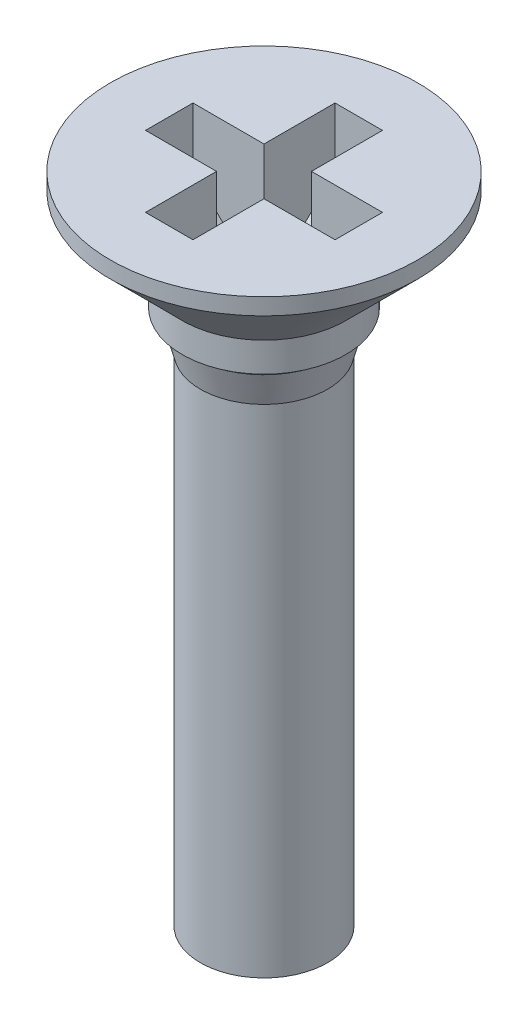
SolidWorks part; units mm, degrees
ref_plane "Vorderseite" through (0, 0, 0) normal (0, 0, 1) x (1, 0, 0)
ref_plane "Oben" through (0, 0, 0) normal (0, 1, 0) x (1, 0, 0)
ref_plane "Rechts" through (0, 0, 0) normal (1, 0, 0) x (0, 0, -1)
sketch "Skizze1" plane through (0, 0, 0) normal (0, 0, 1) x (1, 0, 0)
  line L0 (0, 0) -> (2.35, 0)
  line L1 (2.35, 0) -> (2.35, -0.254)
  line L2 (2.35, -0.254) -> (1.25, -1.354)
  line L3 (1.104, -1.804) -> (1.104, -1.9148)
  line L4 (1.104, -1.9148) -> (0.974, -2.4)
  line L5 (0.974, -2.4) -> (0.974, -10)
  line L6 (0.974, -10) -> (0, -10)
  line L7 (0, 0) -> (0, -10) construction
  line L8 (0, 0) -> (0, -10)
  line L10 (1.25, -1.354) -> (1.25, -1.804)
  line L12 (1.25, -1.804) -> (1.104, -1.804)
  point P3 (1.104, -1.5)
  dimension "D1" = 45
  dimension "D2" = 15
  dimension "K" = 1.5
  dimension "DA" = 4.7
  dimension "DK" = 1.948
  dimension "L" = 10
  dimension "DG" = 2.5
  dimension "A" = 0.9
  dimension "DF" = 2.208
  dimension "P" = 0.45
revolve "Basis-Rotation" add sketch "Skizze1" angle 360 about L7
sketch "Skizze2" plane through (0, 0, 0) normal (0, 0, 1) x (1, 0, 0)
  line L0 (0, -1.8) -> (0, 0) construction
  line L1 (0, 0) -> (0, -10) construction
  line L2 (-0.55, -1.8) -> (0.55, -1.8)
  line L3 (1.45, 0) -> (1.45, -0.9)
  line L4 (1.45, -0.9) -> (0.55, -1.8)
  line L5 (1.45, 0) -> (-1.45, 0)
  line L6 (-1.45, -0.9) -> (-0.55, -1.8)
  line L7 (-1.45, 0) -> (-1.45, -0.9)
  line L8 (0, -0.9) -> (1.45, -0.9) construction
  line L9 (2.35, 0) -> (-2.35, 0) construction
  line L11 (1.25, -1.354) -> (2.35, -0.254) construction
  point P11 (0, 0)
  dimension "M" = 2.9
  dimension "T" = 1.8
extrude "Kreuzschlitz1 H" cut sketch "Skizze2" against normal blind 0.363 and the other way blind 0.363
sketch "Skizze3" plane through (0, 0, 0) normal (1, 0, 0) x (0, 0, -1)
  line L0 (0, -1.8) -> (0, 0) construction
  line L2 (-0.55, -1.8) -> (0.55, -1.8)
  line L3 (1.45, 0) -> (1.45, -0.9)
  line L4 (1.45, -0.9) -> (0.55, -1.8)
  line L5 (1.45, 0) -> (-1.45, 0)
  line L6 (-1.45, -0.9) -> (-0.55, -1.8)
  line L7 (-1.45, 0) -> (-1.45, -0.9)
  line L8 (0, -0.9) -> (1.45, -0.9) construction
  point P11 (0, 0)
extrude "Kreuzschlitz2 H" cut sketch "Skizze3" against normal blind 0.363 and the other way blind 0.363
sketch "Skizze4" plane through (2.4522, 0, -1.8507) normal (0, 1, 0) x (-1, 0, 0)
  line L0 (7.3522, 1.8507) -> (-2.4478, 1.8507) construction
  line L1 (2.4522, -3.0493) -> (2.4522, 6.7507) construction
  line L2 (-2.4478, 1.0342) -> (-2.4478, 2.6672)
  line L3 (-2.4478, 1.0342) -> (0.0059, 1.0342)
  line L4 (0.0059, 1.0342) -> (0.8191, 0.6258)
  line L5 (1.2273, 0.2176) -> (-1.0126, -1.6141)
  line L6 (0.8191, 0.6258) -> (-1.0126, -1.6141)
  line L7 (1.6357, -0.5956) -> (1.2273, 0.2176)
  line L8 (1.6357, -3.0493) -> (1.6357, -0.5956)
  line L9 (1.6357, -3.0493) -> (3.2687, -3.0493)
  line L10 (3.2687, -3.0493) -> (3.2687, -0.5956)
  line L11 (3.2687, -0.5956) -> (3.6772, 0.2176)
  line L12 (2.4522, 1.8507) -> (-1.0126, -1.6141) construction
  line L13 (4.0854, 0.6258) -> (5.917, -1.6141)
  line L14 (3.6772, 0.2176) -> (5.917, -1.6141)
  line L15 (4.8986, 1.0342) -> (4.0854, 0.6258)
  line L16 (7.3522, 1.0342) -> (4.8986, 1.0342)
  line L17 (7.3522, 1.0342) -> (7.3522, 2.6672)
  line L18 (7.3522, 2.6672) -> (4.8986, 2.6672)
  line L19 (4.8986, 2.6672) -> (4.0854, 3.0757)
  line L20 (3.6772, 3.4839) -> (5.917, 5.3156)
  line L21 (4.0854, 3.0757) -> (5.917, 5.3156)
  line L22 (3.2687, 4.2971) -> (3.6772, 3.4839)
  line L23 (3.2687, 6.7507) -> (3.2687, 4.2971)
  line L24 (1.6357, 6.7507) -> (3.2687, 6.7507)
  line L25 (1.6357, 6.7507) -> (1.6357, 4.2971)
  line L26 (1.6357, 4.2971) -> (1.2273, 3.4839)
  line L27 (0.8191, 3.0757) -> (-1.0126, 5.3156)
  line L28 (1.2273, 3.4839) -> (-1.0126, 5.3156)
  line L29 (0.0059, 2.6672) -> (0.8191, 3.0757)
  line L30 (-2.4478, 2.6672) -> (0.0059, 2.6672)
  circle A0 centre (2.4522, 1.8507) radius 4.9 construction
  circle A1 centre (2.4522, 1.8507) radius 2.0415 construction
  circle A2 centre (2.4522, 1.8507) radius 2.579 construction
  dimension "X2" = 4.083
  dimension "X1" = 5.158
  dimension "M" = 9.8
  dimension "D3" = 5.725
  dimension "X3" = 1.633
